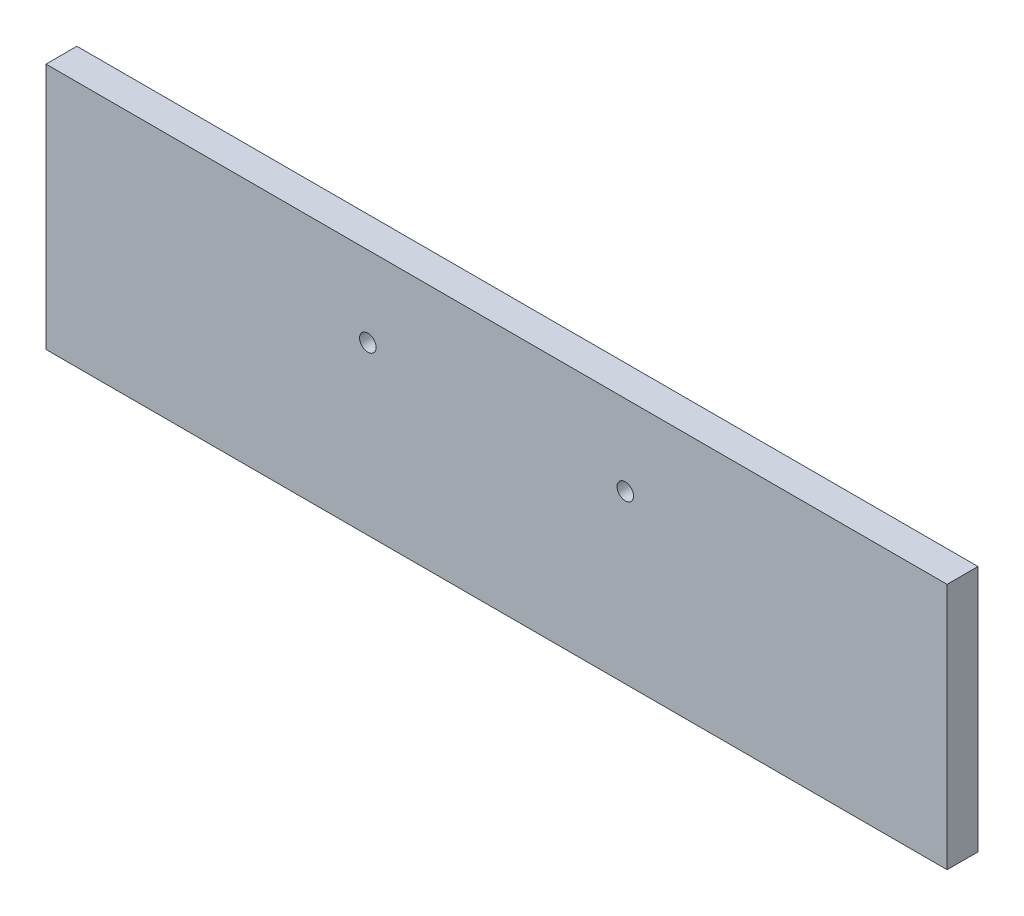
SolidWorks part; units mm, degrees
material "Oak"
ref_plane "Front Plane" through (0, 0, 0) normal (0, 0, 1) x (1, 0, 0)
ref_plane "Top Plane" through (0, 0, 0) normal (0, 1, 0) x (1, 0, 0)
ref_plane "Right Plane" through (0, 0, 0) normal (1, 0, 0) x (0, 0, -1)
sketch "Sketch1" plane through (0, 0, 0) normal (0, 0, 1) x (1, 0, 0)
  line L0 (0, -3.3) -> (0, 3.3) construction
  line L1 (-87.5, -24) -> (87.5, -24)
  line L2 (-87.5, -24) -> (-87.5, 24)
  line L3 (-87.5, 24) -> (87.5, 24)
  line L4 (87.5, -24) -> (87.5, 24)
  line L5 (-87.5, -24) -> (87.5, 24) construction
  line L6 (-87.5, 24) -> (87.5, -24) construction
  circle A0 centre (-25, 8.4) radius 1.6
  circle A1 centre (25, 8.4) radius 1.6
  point P0 (0, 0)
  point P12 (-25, 10)
  dimension "D3" = 25
  dimension "D4" = 3.2
  dimension "D5" = 14
  dimension "D1" = 48
  dimension "D2" = 175
extrude "Boss-Extrude1" add sketch "Sketch1" along normal blind 6
